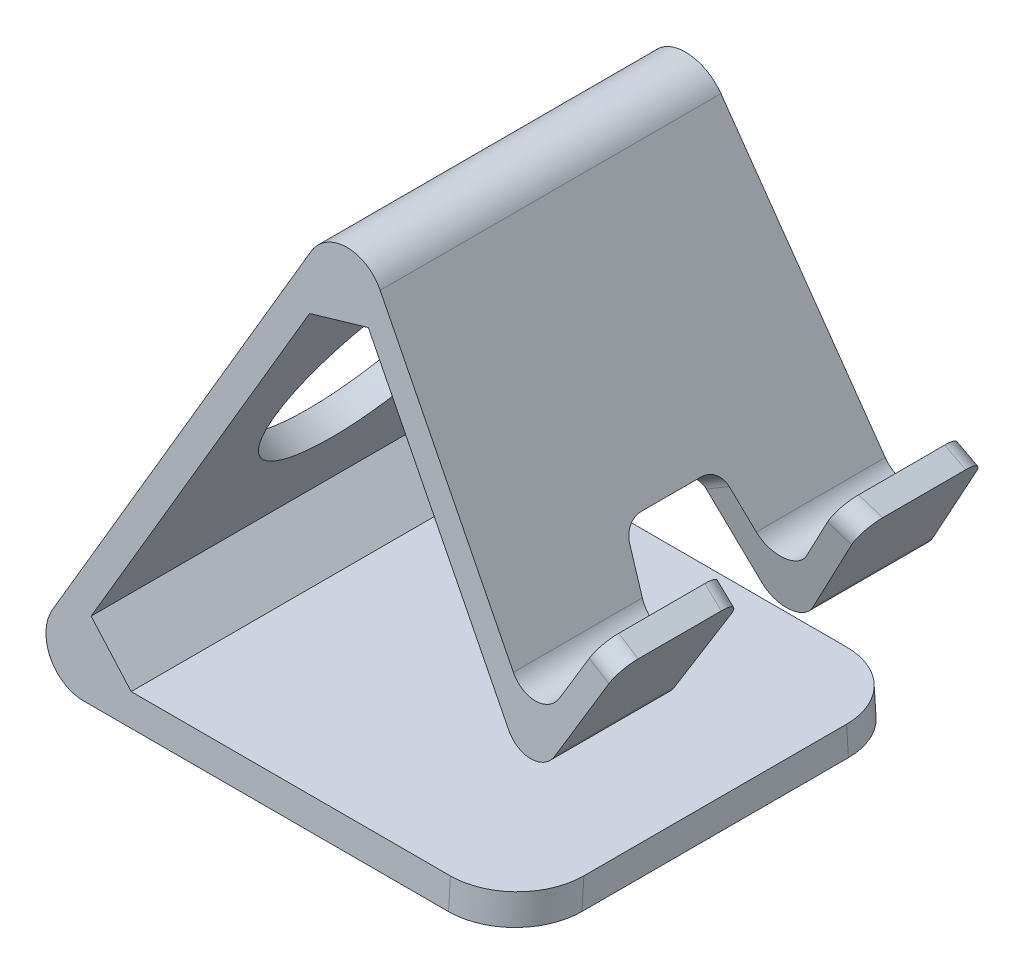
SolidWorks part; units mm, degrees
material "ABS"
ref_plane "前视基准面" through (0, 0, 0) normal (0, 0, 1) x (1, 0, 0)
ref_plane "上视基准面" through (0, 0, 0) normal (0, 1, 0) x (1, 0, 0)
ref_plane "右视基准面" through (0, 0, 0) normal (1, 0, 0) x (0, 0, -1)
other "Configuration Table"
sketch "草图1" plane through (0, 0, 0) normal (0, 0, 1) x (1, 0, 0)
  line L0 (0, 0) -> (45, 80)
  line L1 (45, 80) -> (76.1064, 28)
  line L2 (76.1064, 28) -> (84.9771, 43.3644)
  line L3 (84.9771, 43.3644) -> (88.0081, 41.6144)
  line L4 (88.0081, 41.6144) -> (84.9771, 43.3644)
  line L5 (88.0081, 41.6144) -> (75.8738, 20.5971)
  line L6 (75.8738, 20.5971) -> (45.1064, 72.0303)
  line L7 (45.1064, 72.0303) -> (7.1206, 4.5)
  line L8 (0, 0) -> (75, 0)
  line L9 (75, 0) -> (75, 4.5)
  line L11 (75, 4.5) -> (7.1206, 4.5)
  point P7 (75, 8.0102)
  point P13 (74.7698, 8.0102)
  dimension "D1" = 80
  dimension "D2" = 45
  dimension "D3" = 75
  dimension "D4" = 4
  dimension "D5" = 4.5
  dimension "D6" = 31
  dimension "D7" = 4
  dimension "D8" = 15.5
  dimension "D9" = 3.5
  dimension "D10" = 60
  dimension "D11" = 28
extrude "凸台-拉伸1" add sketch "草图1" along normal mid plane 60 contours L9 L11 L7 L6 L5 L3 L2 L1 L0 L8
sketch "草图2" plane through (75, 0, 0) normal (1, 0, 0) x (0, 0, -1)
  line L0 (-30, 0) -> (-30, 80)
  line L1 (-30, 80) -> (-25, 80)
  line L2 (-30, 80) -> (30, 80) construction
  line L3 (-25, 80) -> (-30, 0)
  line L4 (0, 0) -> (0, 80) construction
  line L5 (25, 80) -> (30, 0)
  line L6 (30, 80) -> (25, 80)
  line L7 (30, 0) -> (30, 80)
  dimension "D1" = 50
extrude "切除-拉伸1" cut sketch "草图2" against normal through all and the other way through all
sketch "草图4" plane through (68.3849, 40.9079, 0) normal (0.8582, 0.5134, 0) x (0, 0, -1)
  line L0 (0, 0) -> (0, -26.6356) construction
  line L1 (7, 0) -> (-7, 0)
  line L2 (-7, 0) -> (-12, -26.6356)
  line L3 (-12, -26.6356) -> (12, -26.6356)
  line L4 (7, 0) -> (12, -26.6356)
  dimension "D1" = 14
  dimension "D2" = 24
extrude "切除-拉伸2" cut sketch "草图4" against normal up to next and the other way through all
fillet "圆角1" radius 10 2 edges at (75, 2.25, -29.8594) (75, 2.25, 29.8594)
chamfer "倒角1" distance 10 angle 45 2 edges at (45.1064, 72.0303, 0) (7.1206, 4.5, 0)
fillet "圆角2" radius 6 2 edges at (0, 0, 0) (45, 80, 0)
fillet "圆角3" radius 4 4 edges at (76.1064, 28, -19.0367) (76.1064, 28, 19.0367) (75.8738, 20.5971, -19.8532) (75.8738, 20.5971, 19.8532)
fillet "圆角4" radius 3 4 edges at (86.4926, 42.4894, -27.3444) (86.4926, 42.4894, -8.4902) (86.4926, 42.4894, 8.4902) (86.4926, 42.4894, 27.3444)
sketch "草图5" plane through (0, 0, 0) normal (0, -1, 0) x (1, 0, 0)
  line L0 (0, 0) -> (94.108, 0) construction
  line L1 (21.5267, 10) -> (21.5267, -10) construction
  line L2 (26.5267, 10) -> (26.5267, -10)
  line L3 (16.5267, 10) -> (16.5267, -10)
  circle A0 centre (65, 19.9805) radius 5
  circle A1 centre (65, -19.9805) radius 5
  arc A3 (26.5267, 10) -> (16.5267, 10) centre (21.5267, 10) ccw
  arc A4 (16.5267, -10) -> (26.5267, -10) centre (21.5267, -10) ccw
  point P9 (21.5267, 0)
  dimension "D1" = 10
  dimension "D2" = 10
  dimension "D3" = 10
  dimension "D4" = 20
extrude "凸台-拉伸2" add sketch "草图5" along normal mid plane 2
sketch "草图6" plane through (0, 0, 0) normal (-0.8716, 0.4903, 0) x (0, 0, 1)
  line L0 (0, 81.4467) -> (0, 10.2591) construction
  line L1 (25.5633, 81.4467) -> (-25.5633, 81.4467) construction
  line L2 (-29.4412, 10.2591) -> (29.4412, 10.2591) construction
  circle A0 centre (0, 45.8529) radius 17.5
  dimension "D1" = 35
extrude "切除-拉伸3" cut sketch "草图6" against normal up to next
sketch "草图7" plane through (0, 0, 0) normal (-0.8716, 0.4903, 0) x (0, 0, 1)
  text T0 "PHONE STAND" font "微软雅黑" height in points 15
extrude "切除-拉伸4" cut sketch "草图7" against normal blind 1
fillet "圆角5" radius 3 2 edges at (66.6686, 39.8812, -7) (66.6686, 39.8812, 7)
